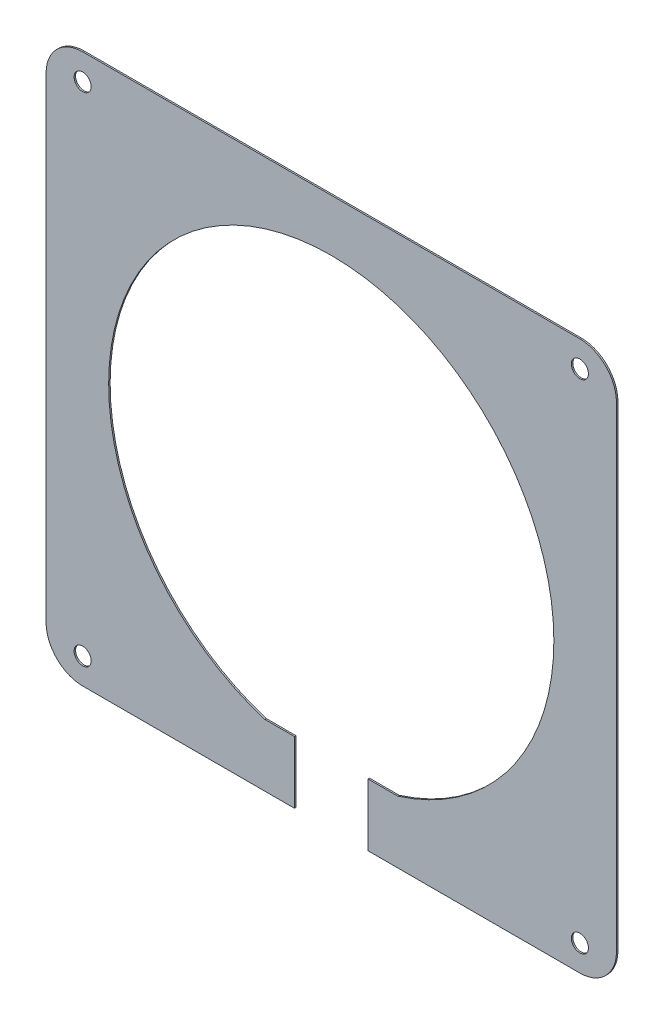
SolidWorks part; units mm, degrees
ref_plane "Front Plane" through (0, 0, 0) normal (0, 0, 1) x (1, 0, 0)
ref_plane "Top Plane" through (0, 0, 0) normal (0, 1, 0) x (1, 0, 0)
ref_plane "Right Plane" through (0, 0, 0) normal (1, 0, 0) x (0, 0, -1)
sketch "Sketch2" plane through (0, 0, 0) normal (0, 0, 1) x (1, 0, 0)
  line L0 (-11.5, -36.7423) -> (11.5, -36.7423)
  line L1 (0, 38.5) -> (0, -36.7423) construction
  line L3 (-49.325, 47.5) -> (49.325, 47.5)
  line L4 (-49.325, 47.5) -> (-49.325, -47.5)
  line L5 (-49.325, -47.5) -> (49.325, -47.5)
  line L6 (49.325, 47.5) -> (49.325, -47.5)
  line L7 (-49.325, 47.5) -> (49.325, -47.5) construction
  line L8 (-49.325, -47.5) -> (49.325, 47.5) construction
  line L9 (-43, 43) -> (43, 43) construction
  line L10 (-43, 43) -> (-43, -43) construction
  line L11 (-43, -43) -> (43, -43) construction
  line L12 (-6.35, -36.7423) -> (-6.35, -47.5)
  line L13 (6.35, -36.7423) -> (6.35, -47.5)
  line L14 (43, 43) -> (43, -43) construction
  line L15 (0, -43) -> (0, 43) construction
  line L16 (-43, 0) -> (43, 0) construction
  circle A0 centre (0, 0) radius 38.5
  circle A1 centre (-43, 43) radius 1.475
  circle A2 centre (43, 43) radius 1.475
  circle A3 centre (43, -43) radius 1.475
  circle A4 centre (-43, -43) radius 1.475
  point P18 (43.9581, 39.6135)
  point P19 (86.8824, 78.2954)
  point P20 (0, 0)
  dimension "D1" = 77
  dimension "D4" = 2.95
  dimension "D3" = 98.65
  dimension "D8" = 12.7
  dimension "D9" = 6.35
  dimension "D10" = 95
  dimension "D2" = 23
  dimension "D5" = 86
extrude "Boss-Extrude1" add sketch "Sketch2" along normal blind 0.254
fillet "Fillet1" radius 6.35 4 edges at (-49.325, -47.5, 0.127) (49.325, -47.5, 0.127) (49.325, 47.5, 0.127) (-49.325, 47.5, 0.127)
equation "\"D9@Sketch2\"=\"D8@Sketch2\"/2"
equation "\"D10@Sketch2\"=97.500mm-1.25*2"
